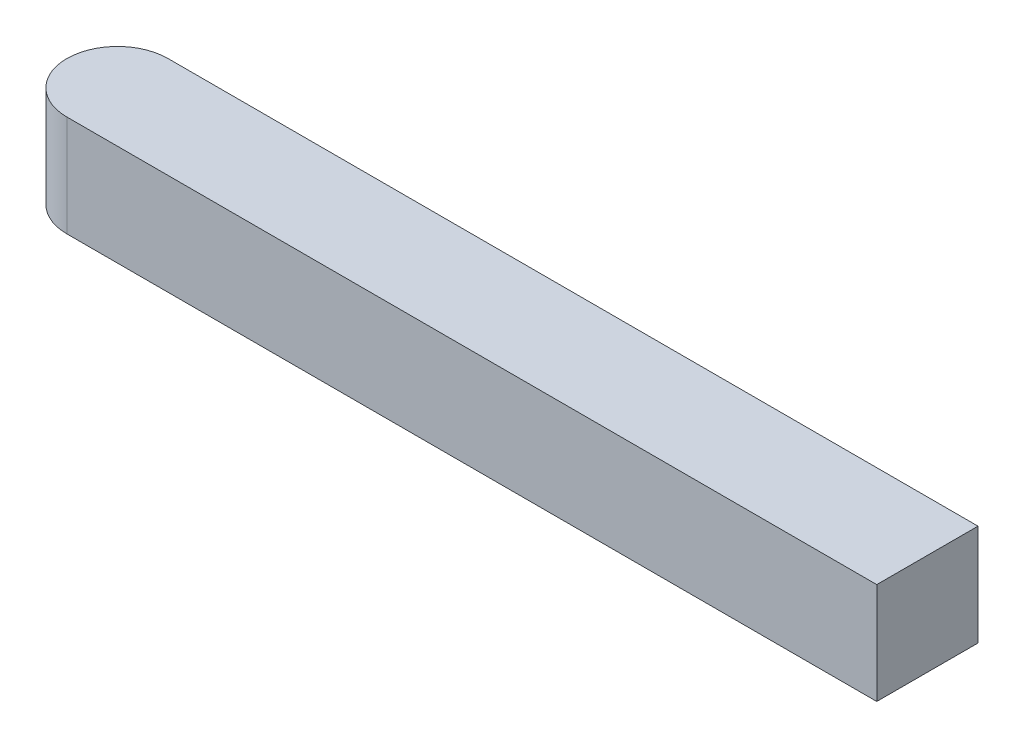
SolidWorks part; units mm, degrees
material "AISI Type A2 Tool Steel"
ref_plane "Front Plane" through (0, 0, 0) normal (0, 0, 1) x (1, 0, 0)
ref_plane "Top Plane" through (0, 0, 0) normal (0, 1, 0) x (1, 0, 0)
ref_plane "Right Plane" through (0, 0, 0) normal (1, 0, 0) x (0, 0, -1)
sketch "Sketch1" plane through (0, 0, 0) normal (0, 1, 0) x (1, 0, 0)
  line L0 (0, 0) -> (-34, 0) construction
  line L1 (0, 2) -> (-32, 2)
  line L2 (0, 2) -> (0, -2)
  line L3 (0, -2) -> (-32, -2)
  arc A0 (-32, 2) -> (-32, -2) centre (-32, 0) ccw
  dimension "D1" = 2
  dimension "D2" = 4
  dimension "D3" = 34
extrude "Boss-Extrude1" add sketch "Sketch1" along normal blind 4
equation "\"D1@Sketch1\" = \"D2@Sketch1\" / 2"
